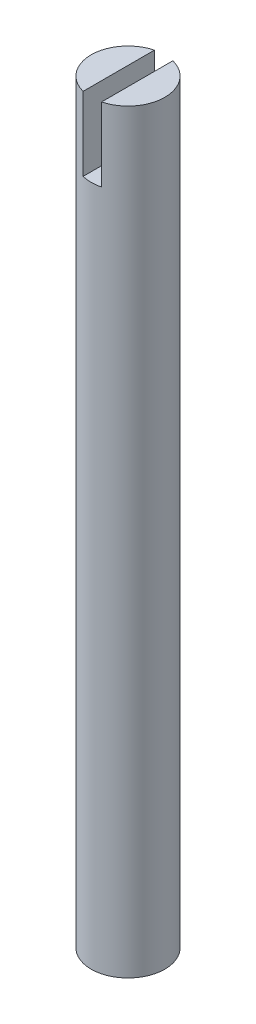
SolidWorks part; units mm, degrees
ref_plane "Front Plane" through (0, 0, 0) normal (0, 0, 1) x (1, 0, 0)
ref_plane "Top Plane" through (0, 0, 0) normal (0, 1, 0) x (1, 0, 0)
ref_plane "Right Plane" through (0, 0, 0) normal (1, 0, 0) x (0, 0, -1)
sketch "Sketch1" plane through (0, 0, 0) normal (0, 1, 0) x (1, 0, 0)
  circle A0 centre (0, 0) radius 10
  dimension "D1" = 20
extrude "Boss-Extrude1" add sketch "Sketch1" along normal blind 205
sketch "Sketch2" plane through (0, 205, 0) normal (0, 1, 0) x (1, 0, 0)
  line L1 (-2.5, 11.535) -> (2.5, 11.535)
  line L2 (-2.5, 11.535) -> (-2.5, -11.535)
  line L3 (-2.5, -11.535) -> (2.5, -11.535)
  line L4 (2.5, 11.535) -> (2.5, -11.535)
  line L5 (0, -11.535) -> (0, 11.535) construction
  line L6 (-2.5, 0) -> (2.5, 0) construction
  point P0 (0, 0)
  dimension "D1" = 23.07
  dimension "D2" = 5
extrude "Cut-Extrude1" cut sketch "Sketch2" against normal blind 20
